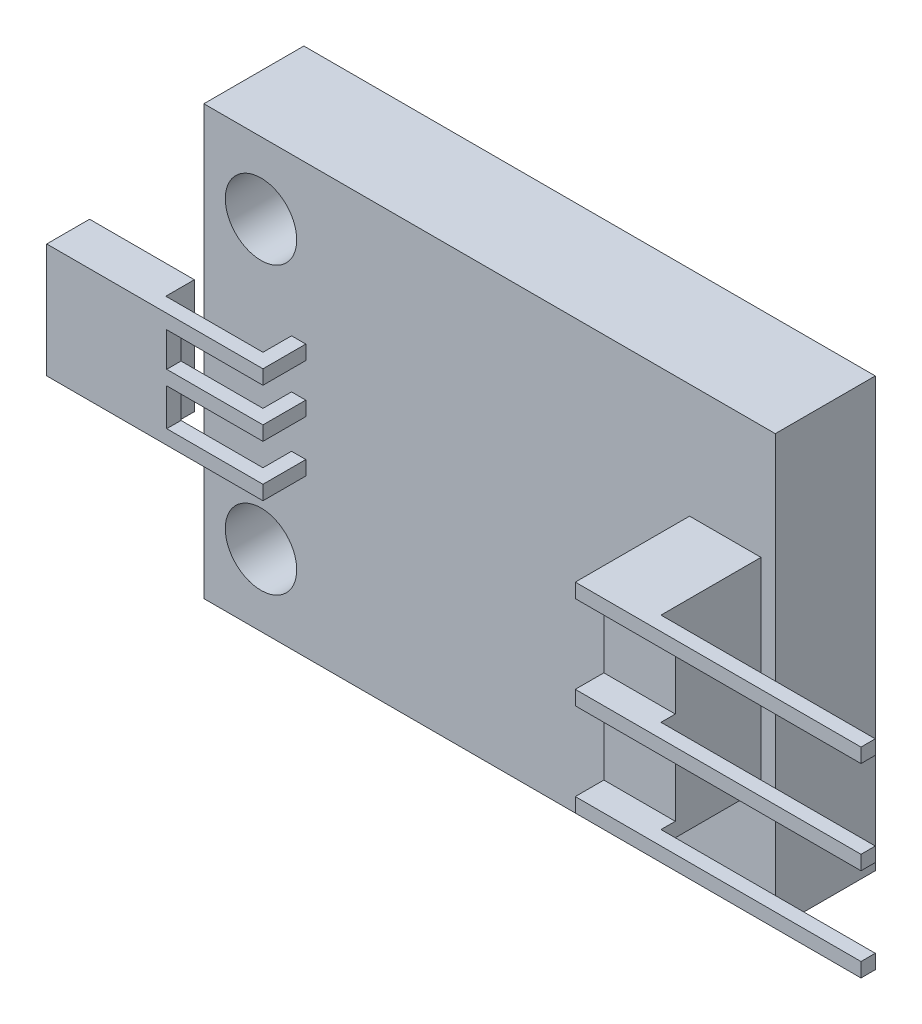
SolidWorks part; units mm, degrees
material "pcb"
ref_plane "Front Plane" through (0, 0, 0) normal (0, 0, 1) x (1, 0, 0)
ref_plane "Top Plane" through (0, 0, 0) normal (0, 1, 0) x (1, 0, 0)
ref_plane "Right Plane" through (0, 0, 0) normal (1, 0, 0) x (0, 0, -1)
sketch "Sketch1" plane through (0, 0, 0) normal (0, 0, 1) x (1, 0, 0)
  line L1 (-10, -7.5) -> (10, -7.5)
  line L2 (-10, -7.5) -> (-10, 7.5)
  line L3 (-10, 7.5) -> (10, 7.5)
  line L4 (10, -7.5) -> (10, 7.5)
  line L5 (-10, -7.5) -> (10, 7.5) construction
  line L6 (-10, 7.5) -> (10, -7.5) construction
  point P0 (0, 0)
  dimension "D1" = 20
  dimension "D2" = 15
extrude "Boss-Extrude1" add sketch "Sketch1" along normal blind 3.5
sketch "Sketch2" plane through (0, 0, 3.5) normal (0, 0, 1) x (1, 0, 0)
  line L0 (-10, 0) -> (-14, 0) construction
  line L1 (-10, 7.5) -> (-10, -7.5) construction
  line L2 (-10, 2) -> (-6.4316, 2)
  line L3 (-14, -2) -> (-10, -2)
  line L4 (-14, -2) -> (-14, 2)
  line L5 (-14, 2) -> (-10, 2)
  line L6 (-10, -2) -> (-10, 2) construction
  line L7 (-14, -2) -> (-10, 2) construction
  line L8 (-14, 2) -> (-10, -2) construction
  line L9 (-6.4316, 2) -> (-6.4316, 1.5)
  line L10 (-6.4316, 1.5) -> (-9.8, 1.5)
  line L12 (-9.8, 0.3) -> (-6.4316, 0.3)
  line L13 (-6.4316, 0.3) -> (-6.4316, -0.2)
  line L14 (-6.4316, -0.2) -> (-9.8, -0.2)
  line L16 (-9.8, -1.5) -> (-6.4316, -1.5)
  line L17 (-6.4316, -1.5) -> (-6.4316, -2)
  line L18 (-6.4316, -2) -> (-10, -2)
  line L19 (-10, 1.5) -> (-10, 0.3)
  line L20 (-9.8, 1.5) -> (-9.8, 0.3)
  line L21 (-9.8, -0.2) -> (-9.8, -1.5)
  point P5 (-12, 0)
  line M19 (-10, 7.5) -> (-10, -7.5)
  dimension "D1" = 4
  dimension "D2" = 4
  dimension "D3" = 0.5
  dimension "D4" = 0.5
  dimension "D5" = 0.2
  dimension "D6" = 0.5
  dimension "D7" = 0.2
extrude "Boss-Extrude8" add sketch "Sketch2" along normal blind 1.5 contours L21 L14 L13 L12 L20 L10 L9 L2 L18 L17 L16 M19 | L5 L4 L3 M19
sketch "Sketch3" plane through (0, -2, 0) normal (0, -1, 0) x (1, 0, 0)
  line L0 (-10.3316, 3.5) -> (-10.3316, 4.5)
  line L1 (-10, 3.5) -> (-14, 3.5) construction
  line L2 (-10.3316, 4.5) -> (-6.9316, 4.5)
  line L3 (-6.9316, 4.5) -> (-6.9316, 3.5)
  line L4 (-10, 3.5) -> (10, 3.5) construction
  line L5 (-6.9316, 3.5) -> (-10.3316, 3.5)
  line L6 (-6.4316, 5) -> (-14, 5) construction
  line L7 (-6.4316, 5) -> (-6.4316, 3.5) construction
  dimension "D1" = 3.4
  dimension "D2" = 0.5
  dimension "D3" = 0.5
extrude "Cut-Extrude1" cut sketch "Sketch3" against normal through all
sketch "Sketch4" plane through (0, 0, 3.5) normal (0, 0, 1) x (1, 0, 0)
  line L0 (10, 0) -> (17, 0) construction
  line L1 (10, -7.5) -> (10, 7.5) construction
  line L2 (10, 0) -> (7, 0) construction
  line L3 (7, -3.5) -> (7, 3.5)
  line L4 (7, 3.5) -> (17, 3.5)
  line L5 (17, 3.5) -> (17, -3.5)
  line L6 (7, -3.5) -> (17, -3.5)
  dimension "D1" = 7
  dimension "D2" = 3
  dimension "D3" = 3.5
extrude "Boss-Extrude9" add sketch "Sketch4" along normal blind 4
sketch "Sketch5" plane through (0, -3.5, 0) normal (0, -1, 0) x (1, 0, 0)
  line L0 (-10, 3.5) -> (10, 3.5) construction
  line L1 (9.5, 3.5) -> (17, 3.5)
  line L2 (9.5, 3.5) -> (9.5, 7)
  line L3 (9.5, 7) -> (17, 7)
  line L4 (17, 3.5) -> (17, 7)
  line L5 (17, 7.5) -> (17, 3.5) construction
  line L6 (7, 7.5) -> (17, 7.5) construction
  line L7 (7, 7.5) -> (7, 3.5) construction
  dimension "D1" = 0.5
  dimension "D2" = 2.5
extrude "Cut-Extrude2" cut sketch "Sketch5" against normal through all
sketch "Sketch6" plane through (0, 0, 7.5) normal (0, 0, 1) x (1, 0, 0)
  line L0 (17, 3) -> (6, 3)
  line L1 (17, -3.5) -> (17, 3.5) construction
  line L2 (6, 3) -> (6, 0.25)
  line L3 (6, 0.25) -> (17, 0.25)
  line L4 (17, 0.25) -> (17, -0.25)
  line L5 (17, -0.25) -> (6, -0.25)
  line L6 (6, -0.25) -> (6, -3)
  line L7 (6, -3) -> (17, -3)
  line L8 (17, -3) -> (18, -3)
  line L9 (18, -3) -> (18, 3)
  line L10 (18, 3) -> (17, 3)
  line L11 (17, 3.5) -> (7, 3.5) construction
  line L12 (7, -3.5) -> (17, -3.5) construction
  line L13 (17, 0) -> (7, 0) construction
  line L14 (7, 3.5) -> (7, -3.5) construction
  line L15 (7, 3.5) -> (7, -3.5) construction
  point P23 (7, 0)
  dimension "D1" = 0.5
  dimension "D2" = 0.5
  dimension "D3" = 0.5
  dimension "D4" = 1
  dimension "D5" = 1
extrude "Cut-Extrude3" cut sketch "Sketch6" against normal blind 1
sketch "Sketch7" plane through (0, 0, 0) normal (0, 0, -1) x (-1, 0, 0)
  line L0 (10, 0) -> (-10, 0) construction
  line L1 (10, 7.5) -> (10, -7.5) construction
  line L2 (-10, -7.5) -> (-10, 7.5) construction
  line L3 (8, 0) -> (8, -5) construction
  circle A0 centre (8, -5) radius 1.25
  circle A1 centre (8, 5) radius 1.25
  dimension "D1" = 2.5
  dimension "D2" = 2
  dimension "D3" = 5
extrude "Cut-Extrude4" cut sketch "Sketch7" against normal through all
